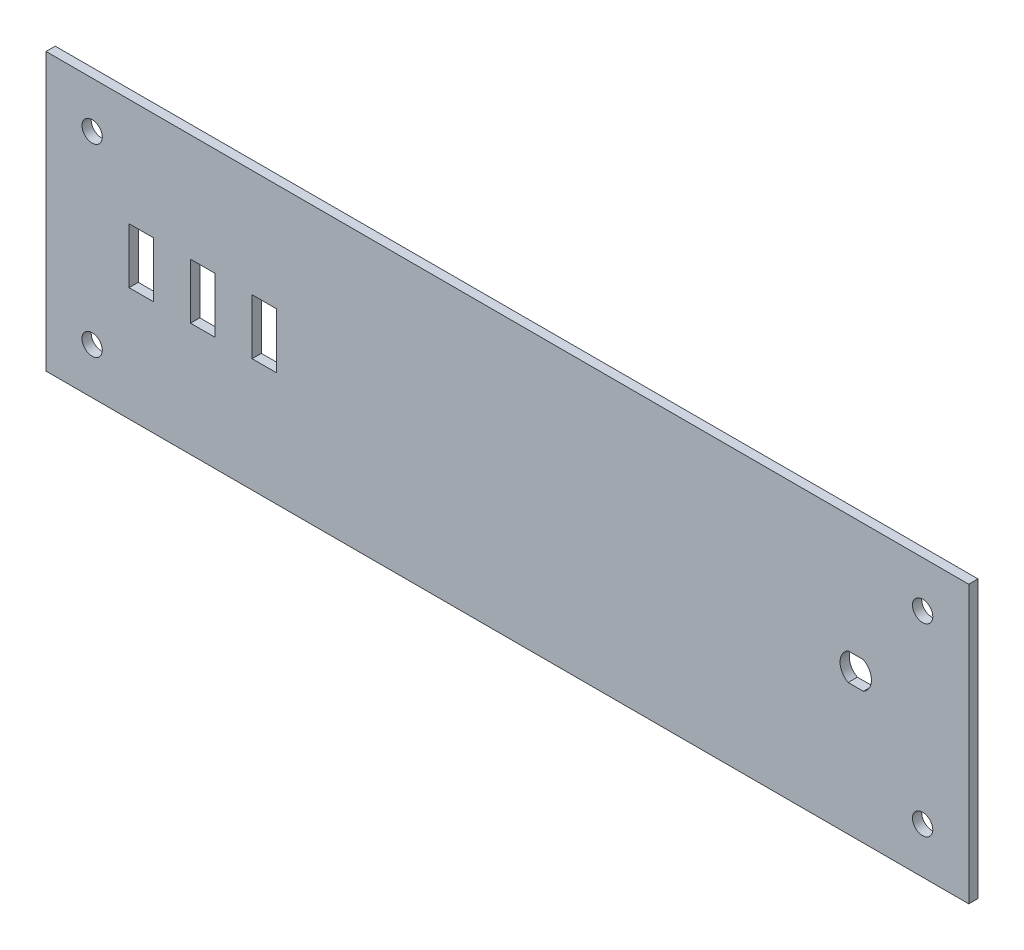
SolidWorks part; units mm, degrees
ref_plane "Ebene vorne" through (0, 0, 0) normal (0, 0, 1) x (1, 0, 0)
ref_plane "Ebene oben" through (0, 0, 0) normal (0, 1, 0) x (1, 0, 0)
ref_plane "Ebene rechts" through (0, 0, 0) normal (1, 0, 0) x (0, 0, -1)
sketch "Skizze1" plane through (0, 0, 0) normal (0, 0, 1) x (1, 0, 0)
  line L0 (-300, -75.0007) -> (0, -75.0007) construction
  line L1 (-300, 15.0008) -> (0, 15.0008)
  line L2 (-300, 15.0008) -> (-300, -75.0007)
  line L3 (-300, -75.0007) -> (0, -75.0007)
  line L4 (0, 15.0008) -> (0, -75.0007)
  dimension "D1" = 0
extrude "Aufsatz-Linear austragen1" add sketch "Skizze1" along normal blind 3 contours L1 L4 L3 L2
hole_wizard "Durchgangsloch für M61" positions "Skizze2" profile "Skizze3" hole size "M6" standard "DIN" end condition up to next
sketch "Skizze2" plane through (0, 0, 3) normal (0, 0, 1) x (1, 0, 0)
  line L0 (-300, 15.0008) -> (-300, -81.0007) construction
  line L1 (-300, -75.0007) -> (0, -75.0007) construction
  line L2 (-278.5725, 15.0008) -> (-297.6644, 15.0008) construction
  line L3 (0, 15.0008) -> (0, -81.0007) construction
  line L4 (0, 15.0008) -> (0, -75.0007) construction
  line L5 (-300, 15.0008) -> (0, 15.0008) construction
  point P0 (-15, 0.0008)
  point P2 (-15, -60.0007)
  point P4 (-285, -60.0007)
  point P6 (-285, 0.0008)
  dimension "D1" = 15
  dimension "D2" = 15
  dimension "D3" = 15
  dimension "D4" = 15
  dimension "D5" = 15
  dimension "D6" = 15
  dimension "D7" = 15
  dimension "D8" = 15
sketch "Skizze3" plane through (-15, 0.0008, 3) normal (1, 0, 0) x (0, -1, 0)
  line L0 (0, 0) -> (0, 3)
  line L1 (0, 3) -> (3.3, 3)
  line L2 (3.3, 3) -> (3.3, 0)
  line L5 (3.3, 0) -> (0, 0)
  line L11 (0, -6.35) -> (0, 107.95) construction
  dimension "Bohrerdurchmesser" = 6.6
  dimension "Bohrungstiefe" = 3
sketch "Skizze4" plane through (0, 0, 3) normal (0, 0, 1) x (1, 0, 0)
  line L0 (-277, 15.0008) -> (-254, 15.0008) construction
  line L1 (-265, -19.9992) -> (-273, -19.9992)
  line L2 (-265, -19.9992) -> (-265, -37.9992)
  line L3 (-265, -37.9992) -> (-273, -37.9992)
  line L4 (-273, -19.9992) -> (-273, -37.9992)
  line L5 (-300, 15.0008) -> (-300, -81.0007) construction
  line L6 (-245, -19.9992) -> (-245, -37.9992)
  line L7 (-245, -37.9992) -> (-253, -37.9992)
  line L8 (-253, -19.9992) -> (-253, -37.9992)
  line L9 (-245, -19.9992) -> (-253, -19.9992)
  line L10 (-225, -19.9992) -> (-225, -37.9992)
  line L11 (-225, -37.9992) -> (-233, -37.9992)
  line L12 (-233, -19.9992) -> (-233, -37.9992)
  line L13 (-225, -19.9992) -> (-233, -19.9992)
  dimension "D1" = 8
  dimension "D2" = 18
  dimension "D3" = 35
  dimension "D4" = 27
  dimension "D5" = 3
  dimension "D6" = 12
  dimension "D7" = 12
extrude "Schnitt-Linear austragen1" cut sketch "Skizze4" against normal blind 10
sketch "Skizze5" plane through (0, 0, 3) normal (0, 0, 1) x (1, 0, 0)
  line L1 (-34.2553, -23.3801) -> (-39.2382, -23.3801)
  line L3 (-34.2553, -32.2801) -> (-39.2382, -32.2801)
  arc A1 (-34.2553, -32.2801) -> (-34.2553, -23.3801) centre (-36.7467, -27.8301) ccw
  arc A2 (-39.2382, -23.3801) -> (-39.2382, -32.2801) centre (-36.7467, -27.8301) ccw
  point P4 (-31.6467, -27.8301)
  point P5 (-41.8467, -27.8301)
  dimension "D1" = 8.9
  dimension "D3" = 10.2
extrude "Schnitt-Linear austragen2" cut sketch "Skizze5" against normal blind 10
